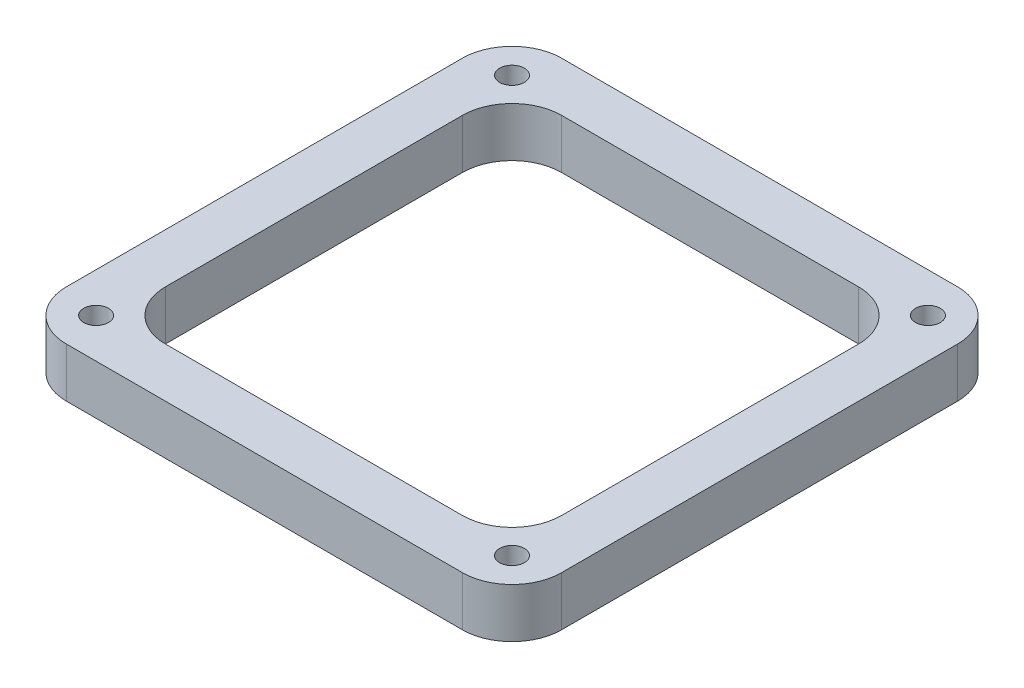
SolidWorks part; units mm, degrees
material "Acrylic (Medium-high impact)"
ref_plane "Front Plane" through (0, 0, 0) normal (0, 0, 1) x (1, 0, 0)
ref_plane "Top Plane" through (0, 0, 0) normal (0, 1, 0) x (1, 0, 0)
ref_plane "Right Plane" through (0, 0, 0) normal (1, 0, 0) x (0, 0, -1)
sketch "Sketch1" plane through (0, 0, 0) normal (0, 1, 0) x (1, 0, 0)
  line L1 (-40, 50) -> (40, 50)
  line L2 (-50, 40) -> (-50, -40)
  line L3 (-40, -50) -> (40, -50)
  line L4 (50, 40) -> (50, -40)
  line L5 (-50, 50) -> (50, -50) construction
  line L6 (-50, -50) -> (50, 50) construction
  arc A0 (-50, -40) -> (-40, -50) centre (-40, -40) ccw
  arc A1 (40, -50) -> (50, -40) centre (40, -40) ccw
  arc A2 (50, 40) -> (40, 50) centre (40, 40) ccw
  arc A3 (-40, 50) -> (-50, 40) centre (-40, 40) ccw
  point P0 (0, 0)
  dimension "D2" = 10
  dimension "D1" = 100
extrude "Boss-Extrude1" add sketch "Sketch1" along normal blind 10
sketch "Sketch2" plane through (0, 10, 0) normal (0, 1, 0) x (1, 0, 0)
  line L1 (-30, -40) -> (30, -40)
  line L2 (-40, -30) -> (-40, 30)
  line L3 (-30, 40) -> (30, 40)
  line L4 (40, -30) -> (40, 30)
  line L5 (-40, -40) -> (40, 40) construction
  line L6 (-40, 40) -> (40, -40) construction
  arc A0 (-40, -30) -> (-30, -40) centre (-30, -30) ccw
  arc A1 (30, -40) -> (40, -30) centre (30, -30) ccw
  arc A2 (40, 30) -> (30, 40) centre (30, 30) ccw
  arc A3 (-30, 40) -> (-40, 30) centre (-30, 30) ccw
  point P0 (0, 0)
  dimension "D2" = 10
  dimension "D1" = 80
extrude "Cut-Extrude1" cut sketch "Sketch2" against normal blind 10
sketch "Sketch3" plane through (0, 10, 0) normal (0, 1, 0) x (1, 0, 0)
  circle A0 centre (-42, 42) radius 2.5
  circle A1 centre (42, 42) radius 2.5
  circle A2 centre (42, -42) radius 2.5
  circle A3 centre (-42, -42) radius 2.5
  dimension "D1" = 5
  dimension "D2" = 42
  dimension "D3" = 42
  dimension "D6" = 84
  dimension "D7" = 84
  dimension "D4" = 2
  dimension "D5" = 2
extrude "Cut-Extrude2" cut sketch "Sketch3" against normal blind 7
